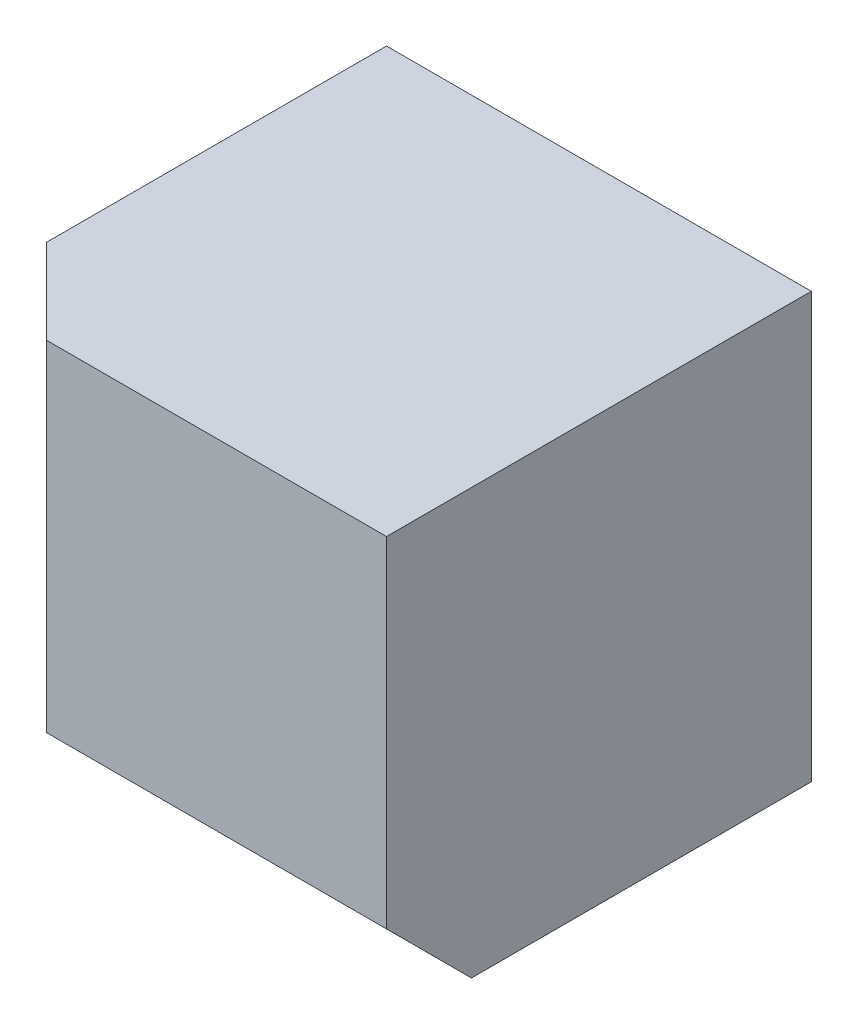
SolidWorks part; units mm, degrees
ref_plane "Front Plane" through (0, 0, 0) normal (0, 0, 1) x (1, 0, 0)
ref_plane "Top Plane" through (0, 0, 0) normal (0, 1, 0) x (1, 0, 0)
ref_plane "Right Plane" through (0, 0, 0) normal (1, 0, 0) x (0, 0, -1)
sketch "Sketch1" plane through (0, 0, 0) normal (0, 0, 1) x (1, 0, 0)
  line L1 (-5, -5) -> (5, -5)
  line L2 (-5, -5) -> (-5, 5)
  line L3 (-5, 5) -> (5, 5)
  line L4 (5, -5) -> (5, 5)
  line L5 (-5, -5) -> (5, 5) construction
  line L6 (-5, 5) -> (5, -5) construction
  point P0 (0, 0)
  dimension "D1" = 10
extrude "Boss-Extrude1" add sketch "Sketch1" along normal blind 10 contours L3 L4 L1 L2
chamfer "Chamfer1" distance 2 angle 45 2 edges at (-5, 0, 10) (0, -5, 10)
